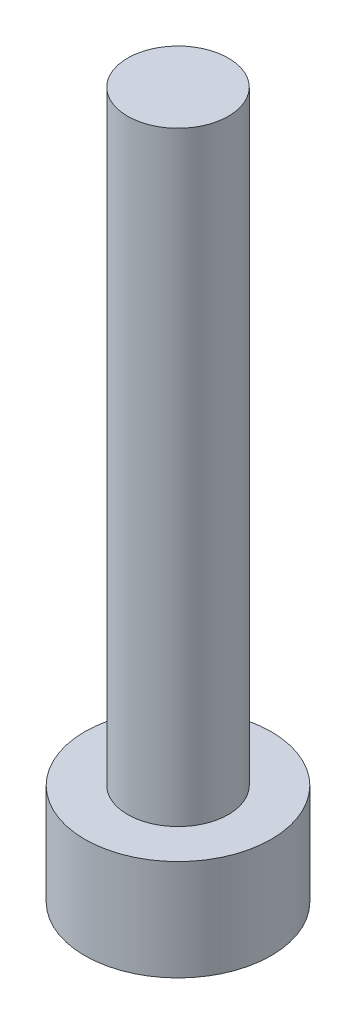
SolidWorks part; units mm, degrees
ref_plane "Front Plane" through (0, 0, 0) normal (0, 0, 1) x (1, 0, 0)
ref_plane "Top Plane" through (0, 0, 0) normal (0, 1, 0) x (1, 0, 0)
ref_plane "Right Plane" through (0, 0, 0) normal (1, 0, 0) x (0, 0, -1)
sketch "Sketch1" plane through (0, 0, 0) normal (0, 1, 0) x (1, 0, 0)
  circle A0 centre (0, 0) radius 1.85
  dimension "D1" = 3.7
extrude "Boss-Extrude1" add sketch "Sketch1" along normal blind 2
sketch "Sketch2" plane through (0, 2, 0) normal (0, 1, 0) x (1, 0, 0)
  circle A0 centre (0, 0) radius 1
  dimension "D1" = 2
extrude "Boss-Extrude2" add sketch "Sketch2" along normal blind 12
